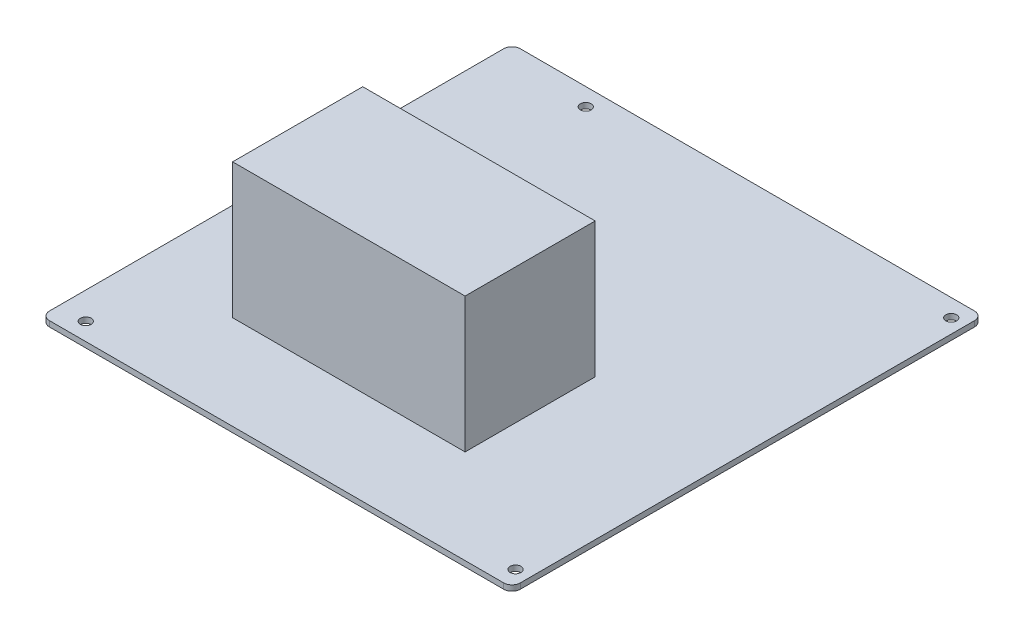
SolidWorks part; units mm, degrees
ref_plane "Front" through (0, 0, 0) normal (0, 0, 1) x (1, 0, 0)
ref_plane "Top" through (0, 0, 0) normal (0, 1, 0) x (1, 0, 0)
ref_plane "Right" through (0, 0, 0) normal (1, 0, 0) x (0, 0, -1)
sketch "Sketch1" plane through (0, 0, 0) normal (0, 1, 0) x (1, 0, 0)
  line L1 (85.09, 85.09) -> (-85.09, 85.09)
  line L2 (85.09, 85.09) -> (85.09, -85.09)
  line L3 (85.09, -85.09) -> (-85.09, -85.09)
  line L4 (-85.09, 85.09) -> (-85.09, -85.09)
  line L5 (85.09, 85.09) -> (-85.09, -85.09) construction
  line L6 (85.09, -85.09) -> (-85.09, 85.09) construction
  point P0 (0, 0)
  dimension "D1" = 170.18
  dimension "D2" = 170.18
extrude "Boss-Extrude1" add sketch "Sketch1" along normal blind 2
sketch "Sketch2" plane through (0, 2, 0) normal (0, 1, 0) x (1, 0, 0)
  line L1 (-49.8792, -4.0694) -> (34.1365, -4.0694)
  line L2 (-49.8792, -4.0694) -> (-49.8792, -51.0882)
  line L3 (-49.8792, -51.0882) -> (34.1365, -51.0882)
  line L4 (34.1365, -4.0694) -> (34.1365, -51.0882)
  line L5 (-49.8792, -4.0694) -> (34.1365, -51.0882) construction
  line L6 (-49.8792, -51.0882) -> (34.1365, -4.0694) construction
  point P0 (-7.8713, -27.5788)
extrude "Boss-Extrude2" add sketch "Sketch2" along normal blind 48.8
fillet "Fillet1" radius 3 4 edges at (-85.09, 1, -85.09) (85.09, 1, -85.09) (85.09, 1, 85.09) (-85.09, 1, 85.09)
hole_wizard "Ø3.9 (3.9) Diameter Hole1" positions "Sketch3" profile "Sketch4" hole size "Ø3.9" standard "ANSI Metric"
sketch "Sketch3" plane through (0, 2, 0) normal (0, 1, 0) x (1, 0, 0)
  line L0 (-82.09, -85.09) -> (82.09, -85.09) construction
  line L1 (85.09, -82.09) -> (85.09, 82.09) construction
  line L3 (-52.07, 78.74) -> (80.01, 78.74) construction
  point P0 (-75.29, -78.74)
  point P2 (80.01, -78.74)
  point P4 (80.01, 78.74)
  point P6 (-52.07, 78.74)
  dimension "D1" = 6.35
  dimension "D2" = 6.35
  dimension "D3" = 5.08
  dimension "D4" = 5.08
  dimension "D5" = 157.48
  dimension "D6" = 132.08
  dimension "D7" = 155.3
sketch "Sketch4" plane through (-75.29, 2, 78.74) normal (1, 0, 0) x (0, 0, 1)
  line L0 (0, 0) -> (0, 19.9217)
  line L1 (0, 19.9217) -> (1.95, 18.75)
  line L2 (1.95, 18.75) -> (1.95, 0)
  line L5 (1.95, 0) -> (0, 0)
  line L10 (0, 19.9217) -> (-1.95, 18.75) construction
  line L11 (0, -6.35) -> (0, 107.95) construction
  dimension "Hole Dia." = 3.9
  dimension "Hole Depth" = 18.75
  dimension "Drill Angle" = 118
